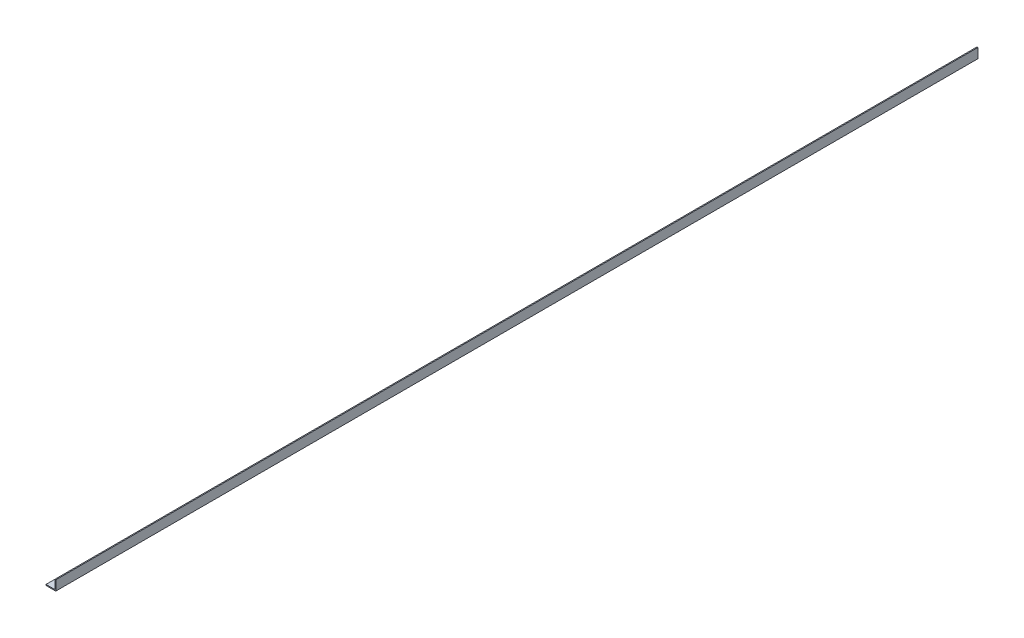
SolidWorks part; units mm, degrees
ref_plane "Alzado" through (0, 0, 0) normal (0, 0, 1) x (1, 0, 0)
ref_plane "Planta" through (0, 0, 0) normal (0, 1, 0) x (1, 0, 0)
ref_plane "Vista lateral" through (0, 0, 0) normal (1, 0, 0) x (0, 0, -1)
sketch "Croquis1" plane through (0, 0, 0) normal (0, 0, 1) x (1, 0, 0)
  line L0 (0, 0) -> (-63.5, 0)
  line L1 (0, 0) -> (0, 63.5)
  line L2 (-6.35, 6.35) -> (-63.5, 6.35)
  line L3 (-6.35, 6.35) -> (-6.35, 63.5)
  line L4 (-6.35, 63.5) -> (0, 63.5)
  line L5 (-63.5, 6.35) -> (-63.5, 0)
  dimension "D1" = 63.5
  dimension "D2" = 63.5
  dimension "D3" = 6.35
extrude "Saliente-Extruir1" add sketch "Croquis1" along normal blind 6000
